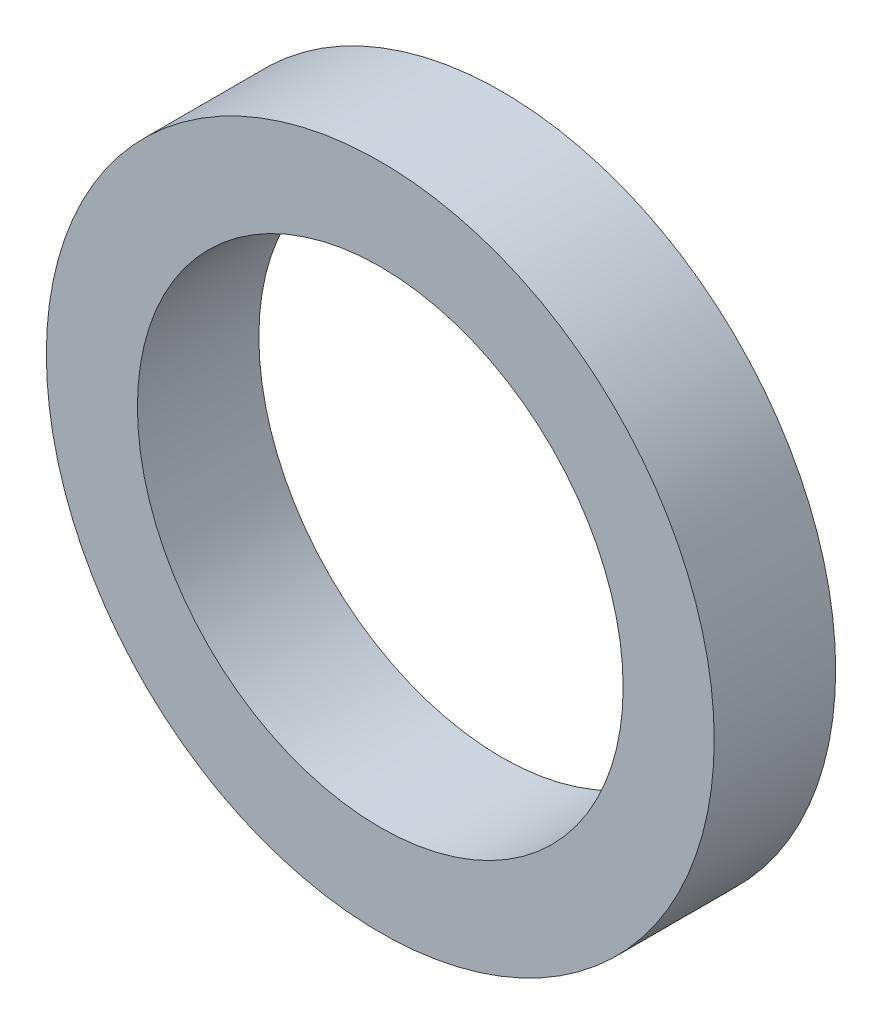
SolidWorks part; units mm, degrees
ref_plane "前视基准面" through (0, 0, 0) normal (0, 0, 1) x (1, 0, 0)
ref_plane "上视基准面" through (0, 0, 0) normal (0, 1, 0) x (1, 0, 0)
ref_plane "右视基准面" through (0, 0, 0) normal (1, 0, 0) x (0, 0, -1)
sketch "草图1" plane through (0, 0, 0) normal (0, 0, 1) x (1, 0, 0)
  circle A0 centre (0, 0) radius 8
  circle A1 centre (0, 0) radius 11
extrude "凸台-拉伸1" add sketch "草图1" along normal blind 4
